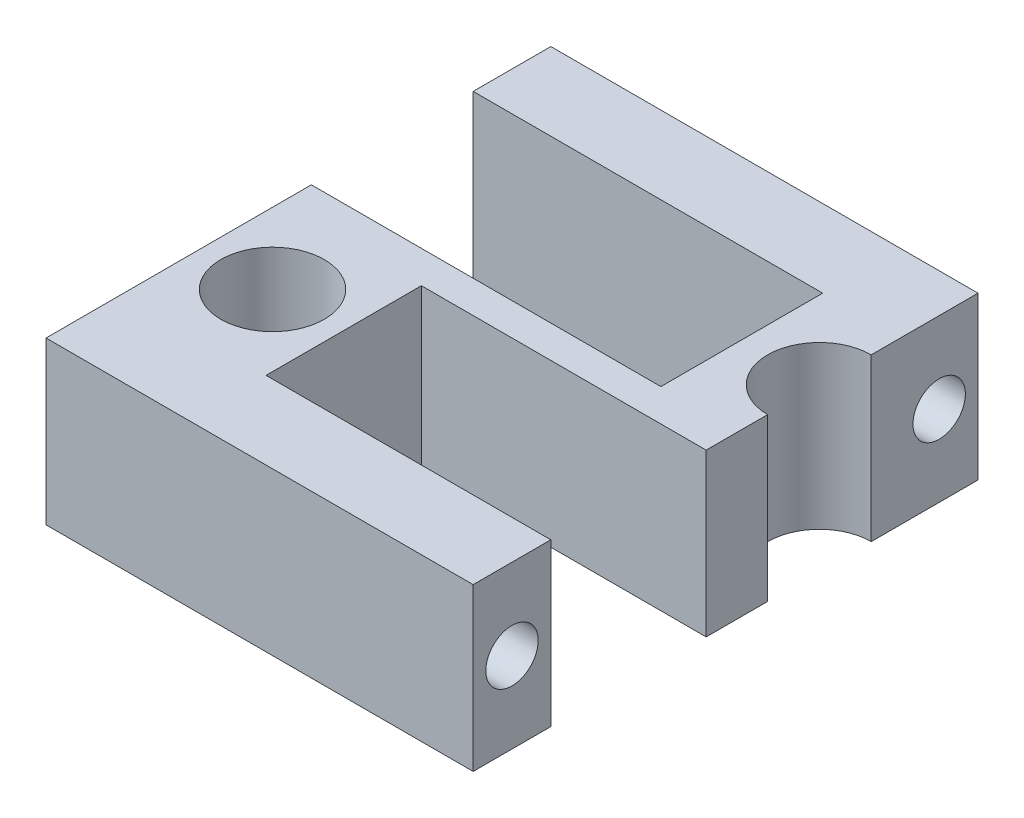
SolidWorks part; units mm, degrees
ref_plane "Front Plane" through (0, 0, 0) normal (0, 0, 1) x (1, 0, 0)
ref_plane "Top Plane" through (0, 0, 0) normal (0, 1, 0) x (1, 0, 0)
ref_plane "Right Plane" through (0, 0, 0) normal (1, 0, 0) x (0, 0, -1)
sketch "Sketch1" plane through (0, 0, 0) normal (0, 1, 0) x (1, 0, 0)
  line L0 (0, 0) -> (0, 24)
  line L1 (0, 24) -> (44, 24)
  line L2 (0, 0) -> (44, 0)
  line L3 (44, 0) -> (44, -12)
  line L4 (44, -12) -> (-22, -12)
  line L5 (-22, 29) -> (32, 29)
  line L6 (32, 29) -> (32, 54)
  line L8 (-22, 29) -> (-22, -12)
  line L9 (44, 24) -> (44, 33.5)
  line L10 (44, 49.5) -> (44, 54)
  line L11 (0, 12) -> (-11, 12) construction
  line L12 (-11, 12) -> (-22, 12) construction
  line L13 (32, 54) -> (-22, 54)
  line L14 (-22, 54) -> (-22, 66)
  line L15 (-22, 66) -> (44, 66)
  line L16 (44, 66) -> (44, 54)
  arc A0 (44, 49.5) -> (44, 33.5) centre (44, 41.5) ccw
  circle A1 centre (-11, 12) radius 8
  point P15 (22, 24)
  point P18 (32, 41.5)
  dimension "D8" = 16
  dimension "D10" = 16
  dimension "D1" = 44
  dimension "D2" = 24
  dimension "D3" = 12
  dimension "D4" = 5
  dimension "D5" = 22
  dimension "D6" = 25
  dimension "D7" = 10
  dimension "D9" = 0
  dimension "D11" = 22
  dimension "D12" = 12
extrude "Boss-Extrude1" add sketch "Sketch1" along normal blind 25
sketch "Sketch2" plane through (44, 0, 0) normal (1, 0, 0) x (0, 0, -1)
  line L0 (0, 25) -> (-12, 0) construction
  line L1 (66, 25) -> (54, 0) construction
  line L2 (49.5, 0) -> (66, 0) construction
  circle A0 centre (-6, 12.5) radius 4.05
  circle A1 centre (60, 12.5) radius 4.05
  dimension "D1" = 8.1
  dimension "D2" = 12
extrude "Cut-Extrude1" cut sketch "Sketch2" against normal blind 76
